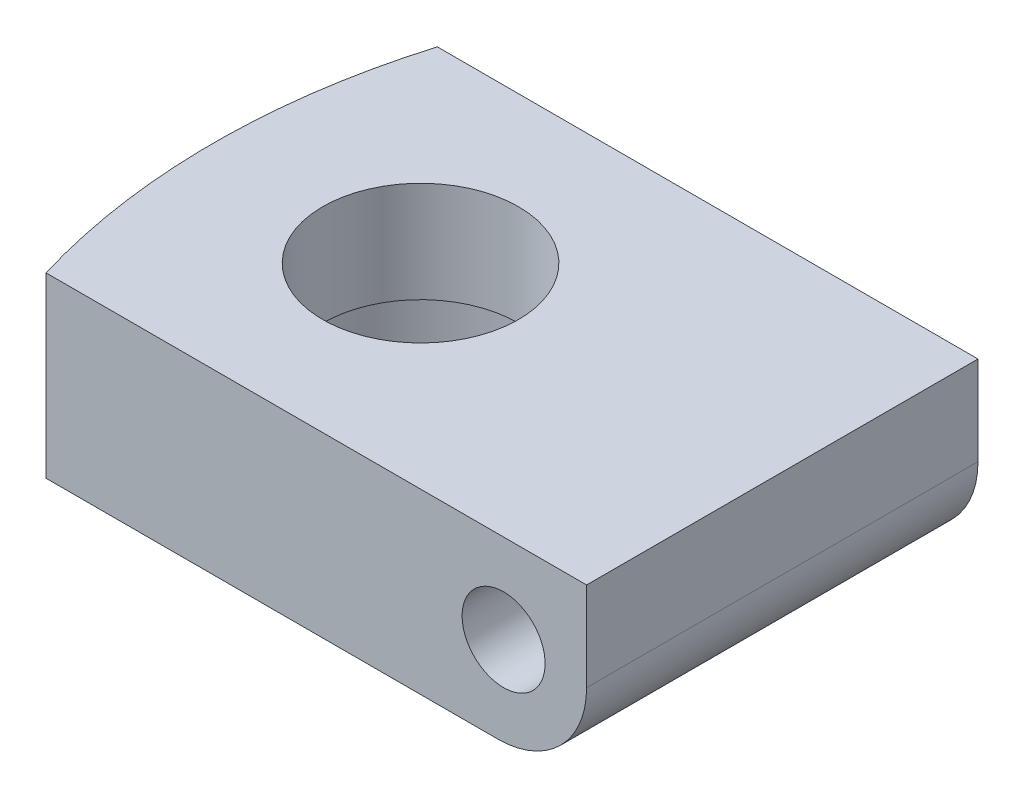
SolidWorks part; units mm, degrees
ref_plane "Front Plane" through (0, 0, 0) normal (0, 0, 1) x (1, 0, 0)
ref_plane "Top Plane" through (0, 0, 0) normal (0, 1, 0) x (1, 0, 0)
ref_plane "Right Plane" through (0, 0, 0) normal (1, 0, 0) x (0, 0, -1)
sketch "Sketch1" plane through (0, 0, 0) normal (0, 1, 0) x (1, 0, 0)
  line L1 (-48, -33) -> (48, -33)
  line L2 (-48, -33) -> (-48, 33) construction
  line L3 (-48, 33) -> (48, 33)
  line L4 (48, -33) -> (48, 33)
  line L5 (-48, -33) -> (48, 33) construction
  line L6 (-48, 33) -> (48, -33) construction
  arc A0 (-43.1635, 33) -> (-43.1635, -33) centre (67, 0) ccw
  point P0 (0, 0)
  dimension "D2" = 115
  dimension "D1" = 66
  dimension "D3" = 96
extrude "Boss-Extrude1" add sketch "Sketch1" along normal blind 30 contours L3 A0 L1 L4
sketch "Sketch2" plane through (0, 0, 0) normal (0, -1, 0) x (1, 0, 0)
  circle A0 centre (-13, 0) radius 22.5
  arc A1 (-43.1635, 33) -> (-43.1635, -33) centre (67, 0) ccw construction
  point P6 (-48, 0)
  dimension "D1" = 45
  dimension "D2" = 35
extrude "Cut-Extrude1" cut sketch "Sketch2" against normal blind 13
sketch "Sketch3" plane through (0, 13, 0) normal (0, -1, 0) x (1, 0, 0)
  circle A0 centre (-13, 0) radius 16.5
  dimension "D1" = 33
extrude "Cut-Extrude2" cut sketch "Sketch3" against normal through all
fillet "Fillet1" radius 15 1 edges at (48, 0, 0)
ref_plane "Plane1" through (0, 15, 0) normal (0, 1, 0) x (1, 0, 0)
sketch "Sketch4" plane through (0, 15, 0) normal (0, 1, 0) x (1, 0, 0)
  line L0 (34, 33) -> (34, -33) construction
  line L1 (-43.1635, 33) -> (48, 33) construction
  line L2 (-43.1635, -33) -> (48, -33) construction
  line L3 (48, -33) -> (48, 33) construction
  line L4 (41, -33) -> (40.34, 33)
  line L5 (40.34, 33) -> (34, 33)
  line L6 (34, -33) -> (41, -33)
  line L7 (34, 33) -> (34, -33)
  dimension "D1" = 14
  dimension "D2" = 14
  dimension "D3" = 12.68
revolve "Cut-Revolve1" cut sketch "Sketch4" angle 360 about L0
